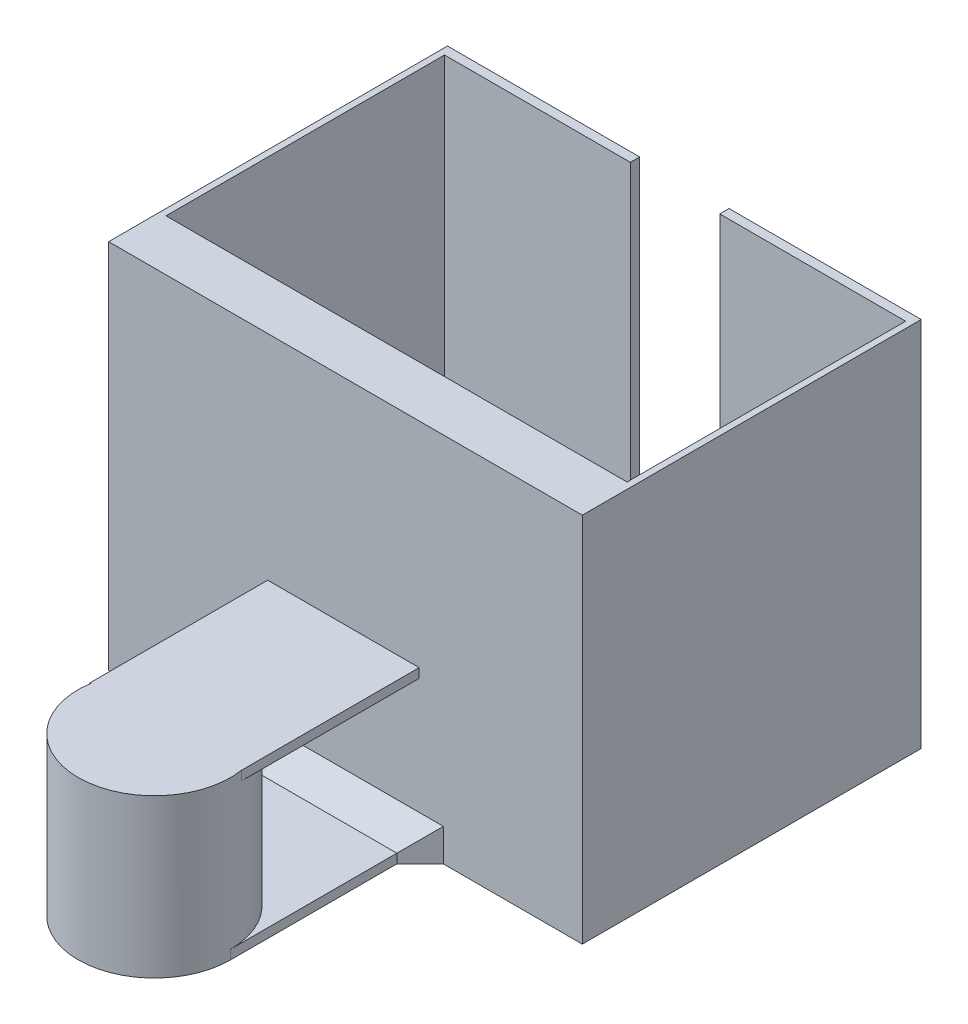
SolidWorks part; units mm, degrees
material "ASTM A36 Steel"
ref_plane "Front Plane" through (0, 0, 0) normal (0, 0, 1) x (1, 0, 0)
ref_plane "Top Plane" through (0, 0, 0) normal (0, 1, 0) x (1, 0, 0)
ref_plane "Right Plane" through (0, 0, 0) normal (1, 0, 0) x (0, 0, -1)
sketch "Sketch2" plane through (0, 0, 0) normal (0, 1, 0) x (1, 0, 0)
  line L0 (66.6966, 107.2229) -> (66.6966, 105.9529)
  line L1 (40.4228, 60.887) -> (105.1928, 60.887)
  line L2 (40.4228, 60.887) -> (40.4228, 107.2229)
  line L3 (40.4228, 107.2229) -> (66.6966, 107.2229)
  line L4 (105.1928, 60.887) -> (105.1928, 107.2229)
  line L5 (66.6966, 105.9529) -> (41.2864, 105.9529)
  line L6 (41.2864, 105.9529) -> (41.2864, 67.872)
  line L7 (41.2864, 67.872) -> (104.3292, 67.872)
  line L8 (104.3292, 67.872) -> (104.3292, 105.9529)
  line L9 (104.3292, 105.9529) -> (78.9191, 105.9529)
  line L10 (78.9191, 105.9529) -> (78.9191, 107.2229)
  line L11 (78.9191, 107.2229) -> (105.1928, 107.2229)
  dimension "D1" = 25.4102
  dimension "D2" = 63.0428
  dimension "D4" = 38.0809
  dimension "D6" = 64.77
  dimension "D5" = 6.985
  dimension "D3" = 1.27
extrude "Boss-Extrude1" add sketch "Sketch2" along normal blind 50.8
sketch "Sketch3" plane through (0, 0, -60.887) normal (0, 0, 1) x (1, 0, 0)
  line L0 (40.4228, 0) -> (105.1928, 0) construction
  line L1 (62.1781, 0) -> (83.0108, 0)
  line L2 (62.1781, 0) -> (62.1781, 1.27)
  line L3 (62.1781, 1.27) -> (83.0108, 1.27)
  line L4 (83.0108, 0) -> (83.0108, 1.27)
  dimension "D1" = 20.8326
  dimension "D2" = 1.27
extrude "Boss-Extrude2" add sketch "Sketch3" along normal blind 25.908
sketch "Sketch5" plane through (0, 0, 0) normal (0, -1, 0) x (1, 0, 0)
  line L0 (62.1781, -34.979) -> (83.0108, -34.979) construction
  circle A1 centre (72.5945, -34.979) radius 10.4163
extrude "Boss-Extrude3" add sketch "Sketch5" against normal blind 21.59
sketch "Sketch14" plane through (0, 21.59, 0) normal (0, 1, 0) x (1, 0, 0)
  line L0 (40.4228, 60.887) -> (105.1928, 60.887) construction
  line L1 (62.1781, 60.887) -> (82.8854, 60.887)
  line L2 (62.1781, 60.887) -> (62.1781, 36.5902)
  line L3 (62.1781, 36.5902) -> (82.8854, 36.5902)
  line L4 (82.8854, 60.887) -> (82.8854, 36.5902)
  line L5 (62.1781, 34.979) -> (62.1781, 60.887) construction
  circle A0 centre (72.5945, 34.979) radius 10.4163 construction
  arc A1 (83.0108, 34.979) -> (62.1781, 34.979) centre (72.5945, 34.979) ccw construction
extrude "Boss-Extrude7" add sketch "Sketch14" against normal blind 1.27
chamfer "Chamfer2" distance 3.175 angle 45 3 edges at (83.0108, 0.635, -60.887) (72.5945, 1.27, -60.887) (62.1781, 0.635, -60.887)
equation "\"SF\"= 4'Safety Factor"
equation "\"Yeild Strength\"= 36000"
equation "\"6_a\"= \"Yeild Strength\" / \"SF\""
equation "\"W\"= 1300'Load"
equation "\"L\"= 0.75'L_min"
equation "\"Z\"= \"W\" * \"L\" / \"6_a\"'Z_min"
equation "\"D_1\"= ( ( 16 / pi ) * \"Z\" ) ^ ( 1 / 3 )"
equation "\"A_2\"= \"W\" / \"6_a\""
equation "\"Depth\"= \"D_1\""
equation "\"Width_2\"= \"A_2\" / \"Depth\""
equation "\"D1@Sketch3\"=\"D_1\""
equation "\"L_3\"= 2.482'By Geometry"
equation "\"Z_3\"= \"W\" * \"L_3\" / ( 4 * \"6_a\" )"
equation "\"H_3\"= ( \"Z_3\" * 6 / \"L_3\" ) ^ ( 1 / 2 )"
equation "\"A_4\"= ( \"W\" / 2 ) / \"6_a\"'A_min"
equation "\"C_m\"= 1.498"
equation "\"W_4\"= \"A_4\" / \"C_m\""
equation "\"C_4\"= 1.49925'C with tol"
equation "\"B_5\"= 1.0004'B with tol"
equation "\"A_5\"= .5008'A with tol"
equation "\"H_5\"= \"A_4\" / \"B_5\""
equation "\"D1@Sketch2\"=\"B_5\""
equation "\"D4@Sketch2\"=\"C_4\""
